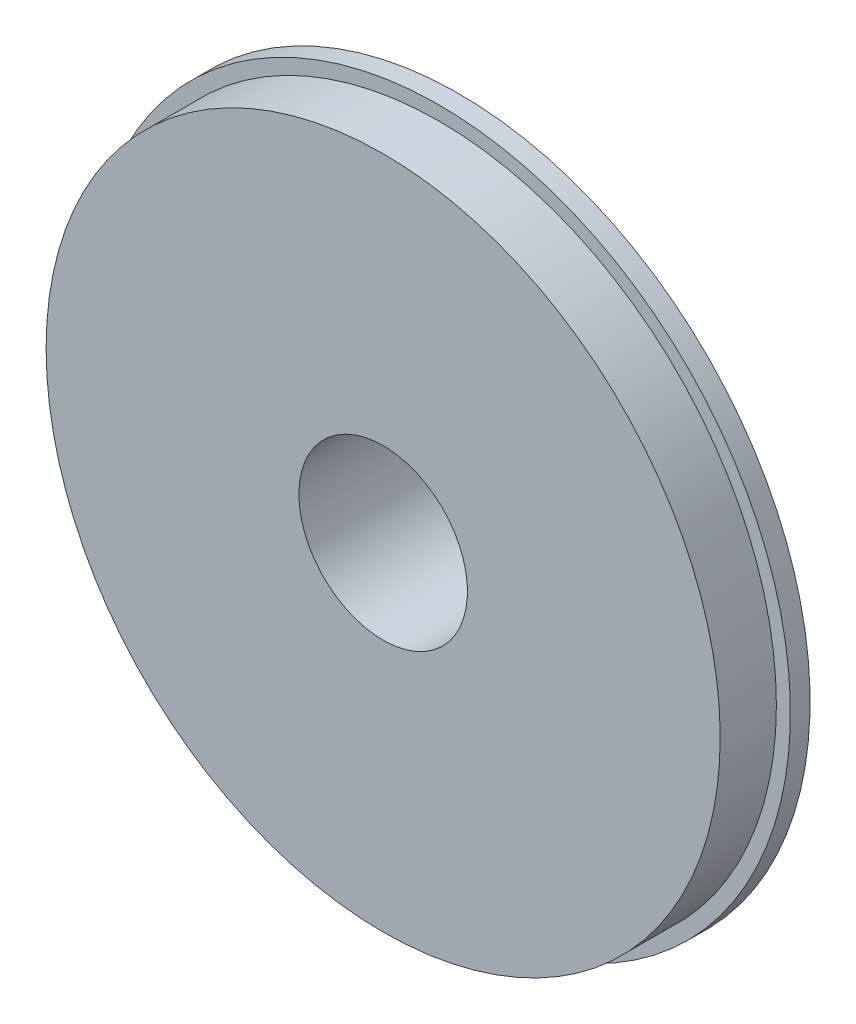
SolidWorks part; units mm, degrees
ref_plane "Front Plane" through (0, 0, 0) normal (0, 0, 1) x (1, 0, 0)
ref_plane "Top Plane" through (0, 0, 0) normal (0, 1, 0) x (1, 0, 0)
ref_plane "Right Plane" through (0, 0, 0) normal (1, 0, 0) x (0, 0, -1)
sketch "Sketch1" plane through (0, 0, 0) normal (0, 0, 1) x (1, 0, 0)
  circle A0 centre (0, 0) radius 12
  dimension "D1" = 24
extrude "Boss-Extrude1" add sketch "Sketch1" along normal blind 2
sketch "Sketch2" plane through (0, 0, 0) normal (0, 0, -1) x (-1, 0, 0)
  circle A0 centre (0, 0) radius 12.5
  circle A1 centre (0, 0) radius 11.5
  dimension "D1" = 23
  dimension "D2" = 25
extrude "Boss-Extrude2" add sketch "Sketch2" along normal blind 0.7
sketch "Sketch3" plane through (0, 0, 0) normal (0, 0, -1) x (-1, 0, 0)
  circle A0 centre (0, 0) radius 3
  dimension "D1" = 6
extrude "Cut-Extrude1" cut sketch "Sketch3" against normal through all
sketch "Sketch4" plane through (0, 0, 0) normal (0, 0, -1) x (-1, 0, 0)
  circle A0 centre (0, 0) radius 7.5
  dimension "D1" = 15
extrude "Boss-Extrude4" add sketch "Sketch4" along normal blind 2.7
sketch "Sketch5" plane through (0, 0, -2.7) normal (0, 0, -1) x (-1, 0, 0)
  circle A0 centre (0, 0) radius 3
  dimension "D1" = 6
extrude "Cut-Extrude3" cut sketch "Sketch5" against normal through all
